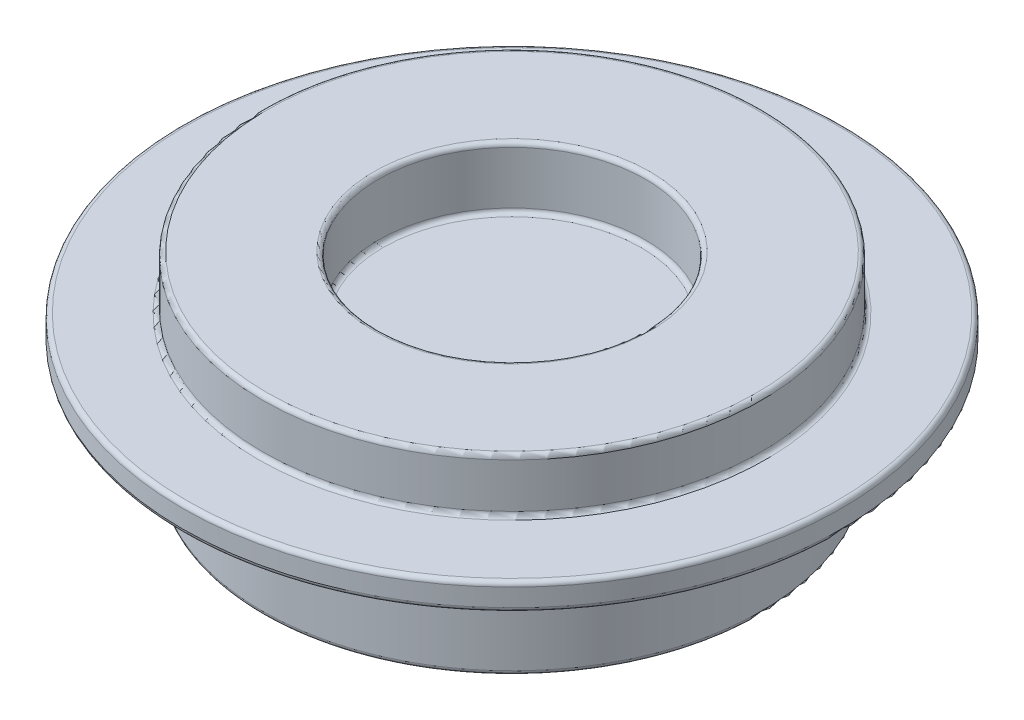
SolidWorks part; units mm, degrees
ref_plane "Front Plane" through (0, 0, 0) normal (0, 0, 1) x (1, 0, 0)
ref_plane "Top Plane" through (0, 0, 0) normal (0, 1, 0) x (1, 0, 0)
ref_plane "Right Plane" through (0, 0, 0) normal (1, 0, 0) x (0, 0, -1)
sketch "Sketch1" plane through (0, 0, 0) normal (0, 0, 1) x (1, 0, 0)
  line L0 (0, 8.1601) -> (0, -7.8301) construction
  line L1 (-14, 4.4927) -> (-7.5, 4.4927)
  line L2 (-14, 4.4927) -> (-14, 1.4927)
  line L3 (-14, 1.4927) -> (-18.5, 1.4927)
  line L4 (-18.5, 1.4927) -> (-18.5, -0.0073)
  line L5 (-18.5, -0.0073) -> (-14, -0.0073)
  line L6 (-14, -0.0073) -> (-14, -6.2573)
  line L7 (-14, -6.2573) -> (0, -6.2573)
  line L8 (-7.5, 4.4927) -> (-7.5, 1.0452)
  line L9 (-7.5, 1.0452) -> (0, 1.0452)
  line L10 (0, 1.0452) -> (0, -6.2573)
  dimension "D1" = 7.5
  dimension "D2" = 6.5
  dimension "D3" = 4.5
  dimension "D4" = 3
  dimension "D5" = 1.5
  dimension "D6" = 6.25
revolve "Revolve1" add sketch "Sketch1" angle 360 about L0
fillet "Fillet1" radius 0.25 8 edges at (0, 1.0452, 7.5) (0, -0.0073, 14) (0, 1.4927, 14) (0, -6.2573, 14) (0, -0.0073, 18.5) (0, 1.4927, 18.5) (0, 4.4927, 14) (0, 4.4927, 7.5)
